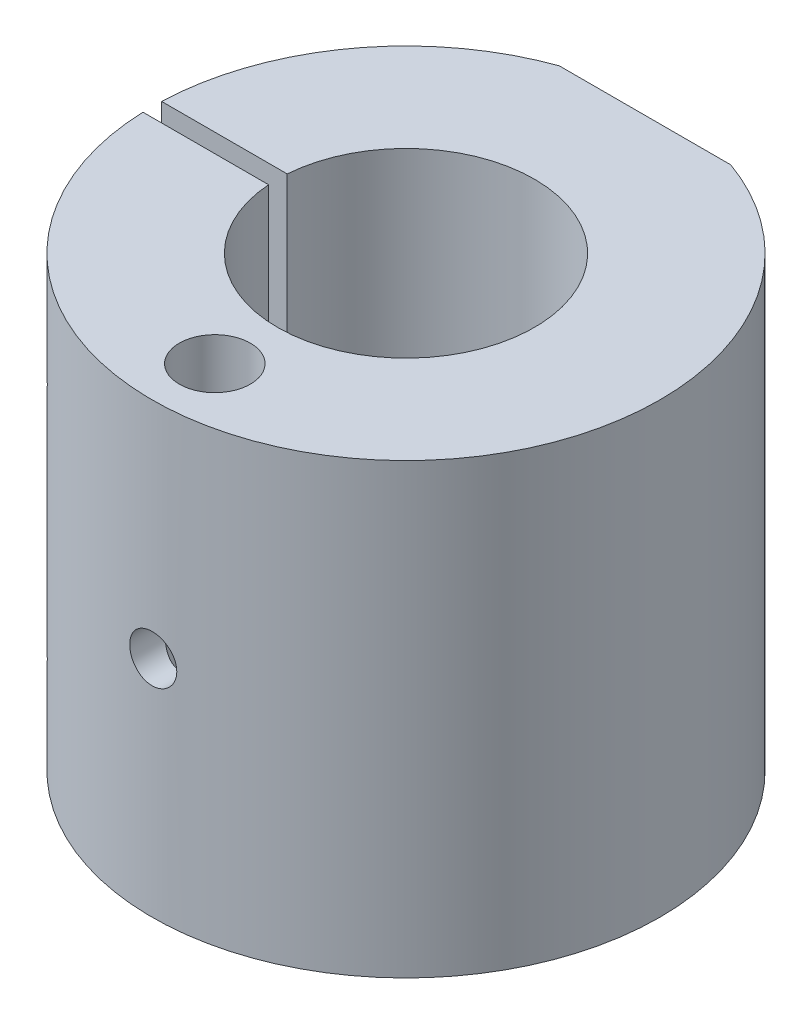
SolidWorks part; units mm, degrees
ref_plane "Front Plane" through (0, 0, 0) normal (0, 0, 1) x (1, 0, 0)
ref_plane "Top Plane" through (0, 0, 0) normal (0, 1, 0) x (1, 0, 0)
ref_plane "Right Plane" through (0, 0, 0) normal (1, 0, 0) x (0, 0, -1)
sketch "Sketch2" plane through (0, 0, 0) normal (0, 1, 0) x (1, 0, 0)
  circle A0 centre (0, 0) radius 10.922
  circle A1 centre (0, 0) radius 21.59
  dimension "D1" = 43.18
  dimension "D2" = 21.844
extrude "Boss-Extrude1" add sketch "Sketch2" along normal blind 38.1
sketch "Sketch3" plane through (0, 38.1, 0) normal (0, 1, 0) x (1, 0, 0)
  line L0 (0, 0) -> (-21.59, 0) construction
  line L1 (0, 0.7937) -> (-21.59, 0.7937)
  line L2 (0, -0.7937) -> (-21.59, -0.7938)
  line L3 (-21.59, 0.7937) -> (-21.59, -0.7938)
  line L4 (0, 0.7937) -> (0, -0.7937)
  circle A0 centre (0, 0) radius 21.59 construction
  dimension "D1" = 0.7937
  dimension "D2" = 0.7937
extrude "Cut-Extrude1" cut sketch "Sketch3" against normal up to next
sketch "Sketch4" plane through (0, 38.1, 0) normal (0, 1, 0) x (1, 0, 0)
  line L0 (0, -10.922) -> (0, -21.59) construction
  arc A0 (-10.8931, -0.7938) -> (-10.8931, 0.7937) centre (0, 0) ccw construction
  arc A1 (-21.5754, -0.7938) -> (-21.5754, 0.7937) centre (0, 0) ccw construction
  circle A2 centre (0, -16.256) radius 3.0226
  dimension "D1" = 6.0452
extrude "Cut-Extrude2" cut sketch "Sketch4" against normal up to next
sketch "Sketch5" plane through (0, 38.1, 0) normal (0, 1, 0) x (1, 0, 0)
  line L0 (7.2956, 20.32) -> (-7.2956, 20.32)
  arc A0 (-21.5754, -0.7938) -> (-21.5754, 0.7937) centre (0, 0) ccw construction
  arc A1 (7.2956, 20.32) -> (-7.2956, 20.32) centre (0, 0) ccw
  dimension "D1" = 20.32
extrude "Cut-Extrude3" cut sketch "Sketch5" against normal up to next
sketch "Sketch6" plane through (0, 0, -20.32) normal (0, 0, -1) x (-1, 0, 0)
  line L0 (0, 38.1) -> (0, 0) construction
  line L1 (7.2956, 38.1) -> (-7.2956, 38.1) construction
  line L2 (-7.2956, 0) -> (7.2956, 0) construction
  circle A0 centre (0, 19.05) radius 0.5591 construction
hole_wizard "Tap Drill for M3x0.5 Tap1" positions "3DSketch1" profile "Sketch7" hole size "M3x0.5" standard "ANSI Metric"
sketch3d "3DSketch1"
  point P0 (0, 19.05, -20.32)
sketch "Sketch7" plane through (0, 19.05, -20.32) normal (1, 0, 0) x (0, 1, 0)
  line L0 (0, 0) -> (0, 5.3231)
  line L1 (0, 5.3231) -> (1.25, 4.572)
  line L2 (1.25, 4.572) -> (1.25, 0)
  line L5 (1.25, 0) -> (0, 0)
  line L10 (0, 5.3231) -> (-1.25, 4.572) construction
  line L11 (0, -6.35) -> (0, 107.95) construction
  dimension "Hole Dia." = 2.5
  dimension "Hole Depth" = 4.572
  dimension "Drill Angle" = 118
ref_plane "Plane1" through (0, 0, 21.59) normal (0, 0, 1) x (1, 0, 0)
sketch "Sketch8" plane through (0, 0, 21.59) normal (0, 0, 1) x (1, 0, 0)
  line L0 (0.0073, 38.1) -> (0.0073, 0) construction
  line L3 (21.59, 38.1) -> (-21.5754, 38.1) construction
  line L4 (-21.5754, 0) -> (21.59, 0) construction
  circle A2 centre (0.0073, 19.05) radius 2
  dimension "D1" = 4
extrude "Cut-Extrude4" cut sketch "Sketch8" against normal up to next
sketch "Sketch9" plane through (0, 0, 0.7937) normal (0, 0, -1) x (-1, 0, 0)
  line L0 (16.2343, 0) -> (16.2343, 38.1) construction
  line L1 (10.8931, 0) -> (21.5754, 0) construction
  line L2 (21.5754, 38.1) -> (10.8931, 38.1) construction
  circle A0 centre (16.2343, 29.1092) radius 1.0697 construction
  circle A1 centre (16.2343, 8.904) radius 1.0697 construction
hole_wizard "Tap Drill for M4x0.7 Tap1" positions "3DSketch4" profile "Sketch10" hole size "M4x0.7" standard "ANSI Metric"
sketch3d "3DSketch4"
  point P0 (-16.2343, 29.1092, 0.7938)
  point P3 (-16.2343, 8.904, 0.7938)
sketch "Sketch10" plane through (-16.2343, 29.1092, 0.7938) normal (1, 0, 0) x (0, 1, 0)
  line L0 (0, 0) -> (0, 13.4392)
  line L1 (0, 13.4392) -> (1.65, 13.4392)
  line L2 (1.65, 13.4392) -> (1.65, 0)
  line L5 (1.65, 0) -> (0, 0)
  line L11 (0, -6.35) -> (0, 107.95) construction
  dimension "Thru Hole Dia." = 3.3
  dimension "Thru Hole Depth" = 13.4392
